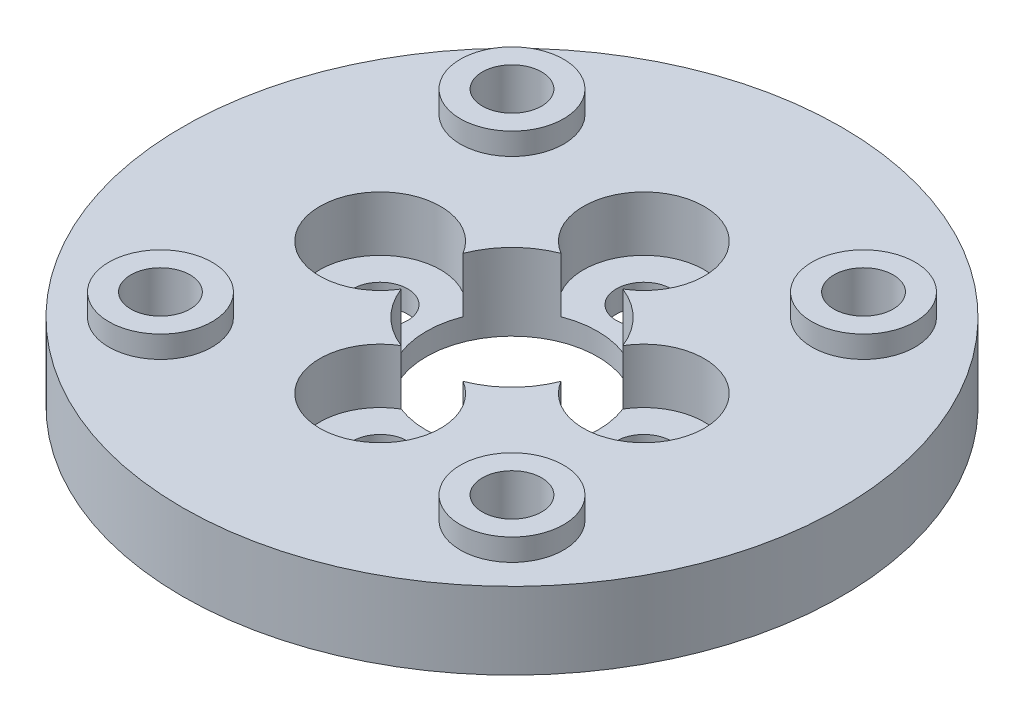
SolidWorks part; units mm, degrees
ref_plane "Front Plane" through (0, 0, 0) normal (0, 0, 1) x (1, 0, 0)
ref_plane "Top Plane" through (0, 0, 0) normal (0, 1, 0) x (1, 0, 0)
ref_plane "Right Plane" through (0, 0, 0) normal (1, 0, 0) x (0, 0, -1)
sketch "Sketch1" plane through (0, 0, 0) normal (0, 1, 0) x (1, 0, 0)
  circle A1 centre (0, 0) radius 15
  dimension "D1" = 30
extrude "Boss-Extrude1" add sketch "Sketch1" along normal blind 3.5
sketch "Sketch2" plane through (0, 3.5, 0) normal (0, 1, 0) x (1, 0, 0)
  line L0 (-6, 0) -> (6, 0) construction
  line L2 (0, 6) -> (0, -6) construction
  line L3 (-8, -8) -> (8, -8) construction
  line L4 (-8, -8) -> (-8, 8) construction
  line L5 (-8, 8) -> (8, 8) construction
  line L6 (8, -8) -> (8, 8) construction
  line L7 (-8, -8) -> (8, 8) construction
  line L8 (-8, 8) -> (8, -8) construction
  circle A0 centre (0, 0) radius 3.9
  point P8 (-6, 0)
  point P9 (0, 6)
  point P10 (0, -6)
  point P11 (6, 0)
  point P15 (0, 0)
  point P16 (-8, 8)
  point P17 (8, 8)
  point P18 (8, -8)
  point P19 (-8, -8)
  point P20 (0, 8)
  dimension "D1" = 7.8
  dimension "D2" = 12
  dimension "D3" = 12
  dimension "D4" = 16
  dimension "D5" = 16
extrude "Cut-Extrude1" cut sketch "Sketch2" against normal through all
hole_wizard "CBORE for M5 Hex Head Bolt1" positions "Sketch3" profile "Sketch5" counterbore size "M5" standard "ANSI Metric" end condition through all
sketch "Sketch3" plane through (0, 3.5, 0) normal (0, 1, 0) x (1, 0, 0)
  point P0 (-6, 0)
  point P3 (0, 6)
  point P6 (6, 0)
  point P9 (0, -6)
sketch "Sketch5" plane through (-6, 3.5, 0) normal (1, 0, 0) x (0, 0, 1)
  line L0 (0, 0) -> (0, 3.5)
  line L1 (0, 3.5) -> (1.25, 3.5)
  line L3 (1.25, 3.5) -> (1.25, 2.5)
  line L4 (1.25, 2.5) -> (2.75, 2.5)
  line L5 (2.75, 2.5) -> (2.75, 0)
  line L7 (2.75, 0) -> (0, 0)
  line L11 (0, -6.35) -> (0, 107.95) construction
  dimension "Thru Hole Dia." = 2.5
  dimension "Thru Hole Depth" = 3.5
  dimension "C'Bore Dia." = 5.5
  dimension "C'Bore Depth" = 2.5
hole_wizard "Tap Drill for M3x0.5 Tap1" positions "Sketch6" profile "Sketch8" hole size "M3x0.5" standard "ANSI Metric" end condition through all
sketch "Sketch6" plane through (0, 3.5, 0) normal (0, 1, 0) x (1, 0, 0)
  point P0 (-8, 8)
  point P3 (8, 8)
  point P6 (8, -8)
  point P9 (-8, -8)
sketch "Sketch8" plane through (-8, 3.5, -8) normal (1, 0, 0) x (0, 0, 1)
  line L0 (0, 0) -> (0, 3.5)
  line L1 (0, 3.5) -> (1.35, 3.5)
  line L2 (1.35, 3.5) -> (1.35, 0)
  line L5 (1.35, 0) -> (0, 0)
  line L11 (0, -6.35) -> (0, 107.95) construction
  dimension "Thru Hole Dia." = 2.7
  dimension "Thru Hole Depth" = 3.5
sketch "Sketch9" plane through (0, 3.5, 0) normal (0, 1, 0) x (1, 0, 0)
  circle A0 centre (8, -8) radius 1.35 construction
  circle A1 centre (8, 8) radius 1.35 construction
  circle A2 centre (-8, -8) radius 1.35 construction
  circle A3 centre (-8, 8) radius 1.35 construction
  circle A4 centre (8, -8) radius 1.35
  circle A5 centre (8, 8) radius 1.35
  circle A6 centre (-8, -8) radius 1.35
  circle A7 centre (-8, 8) radius 1.35
  circle A8 centre (8, -8) radius 2.35
  circle A9 centre (8, 8) radius 2.35
  circle A10 centre (-8, -8) radius 2.35
  circle A11 centre (-8, 8) radius 2.35
  dimension "D1" = 1
extrude "Boss-Extrude2" add sketch "Sketch9" along normal blind 1
